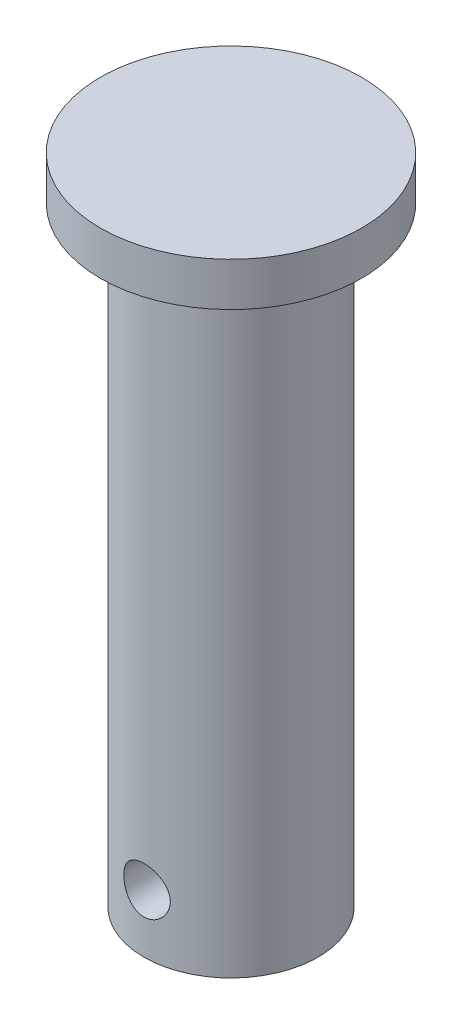
SolidWorks part; units mm, degrees
material "1023 Carbon Steel Sheet (SS)"
ref_plane "Front Plane" through (0, 0, 0) normal (0, 0, 1) x (1, 0, 0)
ref_plane "Top Plane" through (0, 0, 0) normal (0, 1, 0) x (1, 0, 0)
ref_plane "Right Plane" through (0, 0, 0) normal (1, 0, 0) x (0, 0, -1)
sketch "Sketch1" plane through (0, 0, 0) normal (0, 1, 0) x (1, 0, 0)
  circle A0 centre (0, 0) radius 6
  dimension "D1" = 12
extrude "Boss-Extrude1" add sketch "Sketch1" along normal blind 42
sketch "Sketch2" plane through (0, 42, 0) normal (0, 1, 0) x (1, 0, 0)
  circle A0 centre (0, 0) radius 9
  dimension "D1" = 18
extrude "Boss-Extrude2" add sketch "Sketch2" along normal blind 3
sketch "Sketch3" plane through (0, 0, 0) normal (0, 0, 1) x (1, 0, 0)
  line L0 (-6, 42) -> (-6, 0) construction
  line L1 (-6, 42) -> (6, 42) construction
  circle A0 centre (0, 4) radius 1.6
  dimension "D1" = 3.2
  dimension "D2" = 6
  dimension "D3" = 38
extrude "Cut-Extrude1" cut sketch "Sketch3" against normal through all both and the other way through all
